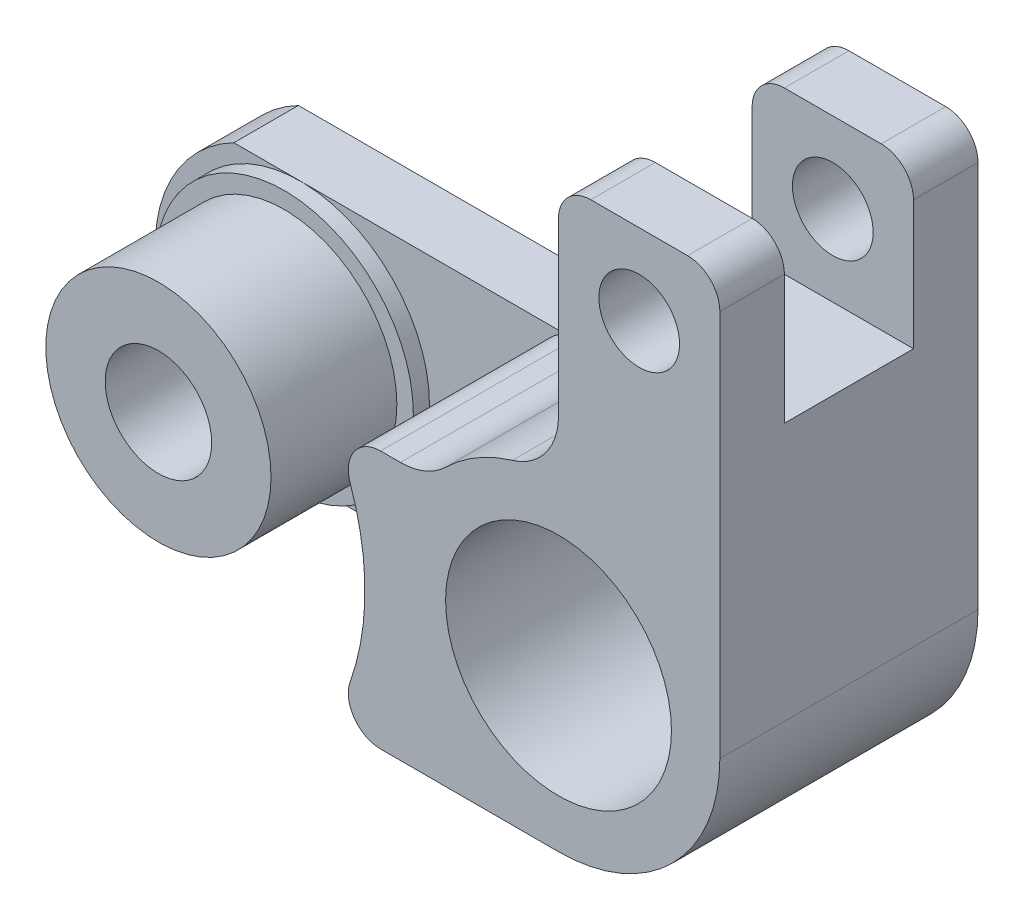
SolidWorks part; units mm, degrees
ref_plane "Plan de face" through (0, 0, 0) normal (0, 0, 1) x (1, 0, 0)
ref_plane "Plan de dessus" through (0, 0, 0) normal (0, 1, 0) x (1, 0, 0)
ref_plane "Plan de droite" through (0, 0, 0) normal (1, 0, 0) x (0, 0, -1)
sketch "Esquisse1" plane through (0, 0, 0) normal (0, 0, 1) x (1, 0, 0)
  line L0 (0, 0) -> (24, 0)
  line L1 (24, 0) -> (24, 18)
  line L2 (24, 18) -> (19, 18)
  line L3 (19, 18) -> (19, 8)
  line L4 (19, 8) -> (0, 8)
  line L5 (0, 8) -> (0, 0)
  dimension "D1" = 8
  dimension "D2" = 5
  dimension "D3" = 24
  dimension "D4" = 18
extrude "Boss.-Extru.1" add sketch "Esquisse1" along normal blind 8
sketch "Esquisse2" plane through (0, 0, 8) normal (0, 0, 1) x (1, 0, 0)
  line L0 (0, 0) -> (24, 0) construction
  line L1 (24, 0) -> (24, 18) construction
  circle A0 centre (19, 5) radius 5
  dimension "D3" = 10
  dimension "D1" = 5
  dimension "D2" = 5
extrude "Boss.-Extru.2" add sketch "Esquisse2" against normal up to vertex (8 mm away) up to point (19, 8, 0)
sketch "Esquisse3" plane through (0, 0, 8) normal (0, 0, 1) x (1, 0, 0)
  circle A0 centre (19, 5) radius 3.5
  arc A1 (19, 10) -> (15, 8) centre (19, 5) ccw construction
  dimension "D1" = 7
extrude "Enlèv. mat.-Extru.1" cut sketch "Esquisse3" against normal blind 7
sketch "Esquisse4" plane through (0, 0, 1) normal (0, 0, 1) x (1, 0, 0)
  circle A0 centre (19, 5) radius 2.5
  dimension "D1" = 5
extrude "Enlèv. mat.-Extru.2" cut sketch "Esquisse4" against normal through all both and the other way through all
sketch "Esquisse5" plane through (0, 0, 8) normal (0, 0, 1) x (1, 0, 0)
  line L0 (0, 0) -> (24, 0) construction
  line L1 (0, 8) -> (0, 0) construction
  circle A0 centre (5, 4) radius 8
  dimension "D2" = 5
  dimension "D3" = 16
  dimension "D1" = 4
extrude "Enlèv. mat.-Extru.3" cut sketch "Esquisse5" against normal blind 6
sketch "Esquisse6" plane through (0, 0, 2) normal (0, 0, 1) x (1, 0, 0)
  circle A0 centre (5, 4) radius 3.49
  arc A1 (11.9282, 0) -> (11.9282, 8) centre (5, 4) ccw construction
  dimension "D1" = 6.98
extrude "Boss.-Extru.3" add sketch "Esquisse6" along normal blind 4.4
sketch "Esquisse7" plane through (0, 0, 6.4) normal (0, 0, 1) x (1, 0, 0)
  circle A0 centre (5, 4) radius 1.65
  dimension "D1" = 3.3
extrude "Enlèv. mat.-Extru.4" cut sketch "Esquisse7" against normal through all both and the other way through all
sketch "Esquisse8" plane through (0, 0, 2) normal (0, 0, 1) x (1, 0, 0)
  line L1 (0, 8) -> (2.9384, 8)
  line L2 (0, 0) -> (2.9384, 0)
  line L3 (0, 0) -> (0, 8)
  circle A1 centre (5, 4) radius 4.5 construction
  arc A2 (2.9384, 0) -> (2.9384, 8) centre (5, 4) cw
  dimension "D1" = 9
extrude "Enlèv. mat.-Extru.5" cut sketch "Esquisse8" against normal through all both and the other way through all
fillet "Congé1" radius 5 1 edges at (24, 0, 4)
fillet "Congé2" radius 1 4 edges at (11.9282, 8, 5) (11.9282, 0, 5) (24, 18, 4) (19, 18, 4)
sketch "Esquisse9" plane through (0, 18, 0) normal (0, 1, 0) x (1, 0, 0)
  line L0 (20, -4) -> (23, -4) construction
  line L1 (20, 0) -> (20, -8) construction
  line L2 (23, -8) -> (23, 0) construction
  line L3 (21.5, -6) -> (21.5, -2) construction
  line L4 (19, -2) -> (24, -2)
  line L5 (24, 0) -> (24, -8) construction
  line L6 (24, -2) -> (24, -6)
  line L7 (19, -2) -> (19, -6)
  line L8 (19, -6) -> (24, -6)
  point P15 (21.5, -4)
  point P16 (19, -4)
  point P17 (24, -4)
  dimension "D1" = 4
extrude "Enlèv. mat.-Extru.6" cut sketch "Esquisse9" against normal blind 5
fillet "Congé3" radius 2 2 edges at (19, 10, 4) (15, 8, 4)
sketch "Esquisse10" plane through (0, 0, 8) normal (0, 0, 1) x (1, 0, 0)
  line L0 (21.5, 18) -> (21.5, 15.5) construction
  line L1 (23, 18) -> (20, 18) construction
  circle A0 centre (21.5, 15.5) radius 1.25
  dimension "D1" = 2.5
  dimension "D2" = 2.5
extrude "Enlèv. mat.-Extru.7" cut sketch "Esquisse10" against normal through all both and the other way through all
sketch "Esquisse11" plane through (0, 0, 6.4) normal (0, 0, 1) x (1, 0, 0)
  circle A1 centre (5, 4) radius 3.49
  circle A2 centre (5, 4) radius 4
  dimension "D1" = 6.98
  dimension "D2" = 8
extrude "Boss.-Extru.4" add sketch "Esquisse11" along normal blind 0.5 from surface at -4.4 separate body starting at face at (9.2102, 4, 2)
